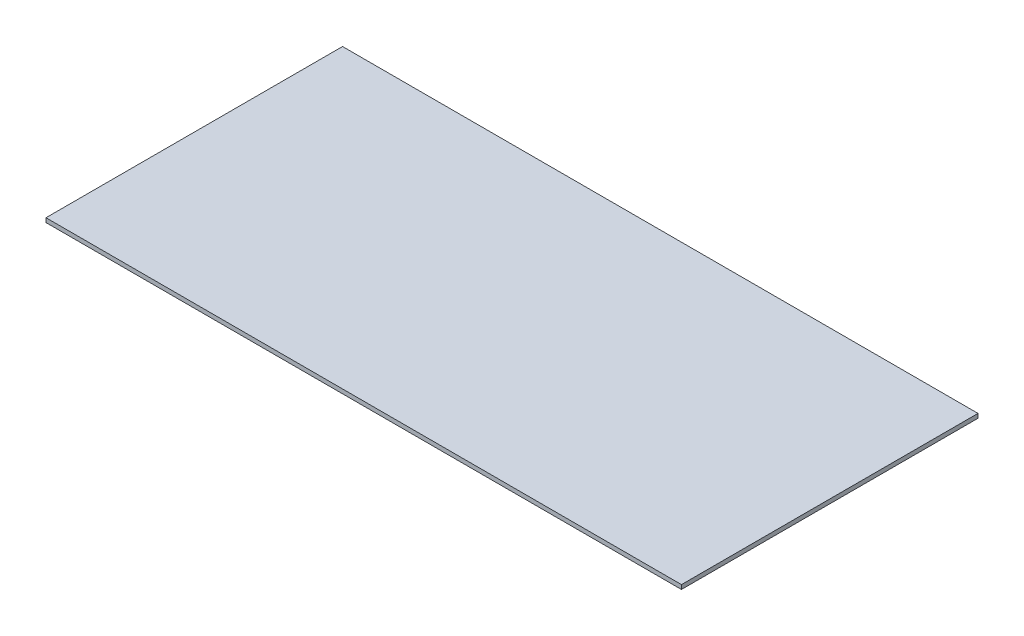
SolidWorks part; units mm, degrees
ref_plane "前视基准面" through (0, 0, 0) normal (0, 0, 1) x (1, 0, 0)
ref_plane "上视基准面" through (0, 0, 0) normal (0, 1, 0) x (1, 0, 0)
ref_plane "右视基准面" through (0, 0, 0) normal (1, 0, 0) x (0, 0, -1)
other "Configuration Table"
sketch "草图1" plane through (0, 0, 0) normal (0, 0, 1) x (1, 0, 0)
  line L1 (-450, -3) -> (450, -3)
  line L2 (-450, -3) -> (-450, 3)
  line L3 (-450, 3) -> (450, 3)
  line L4 (450, -3) -> (450, 3)
  line L5 (-450, -3) -> (450, 3) construction
  line L6 (-450, 3) -> (450, -3) construction
  point P0 (0, 0)
extrude "凸台-拉伸1" add sketch "草图1" along normal blind 420
